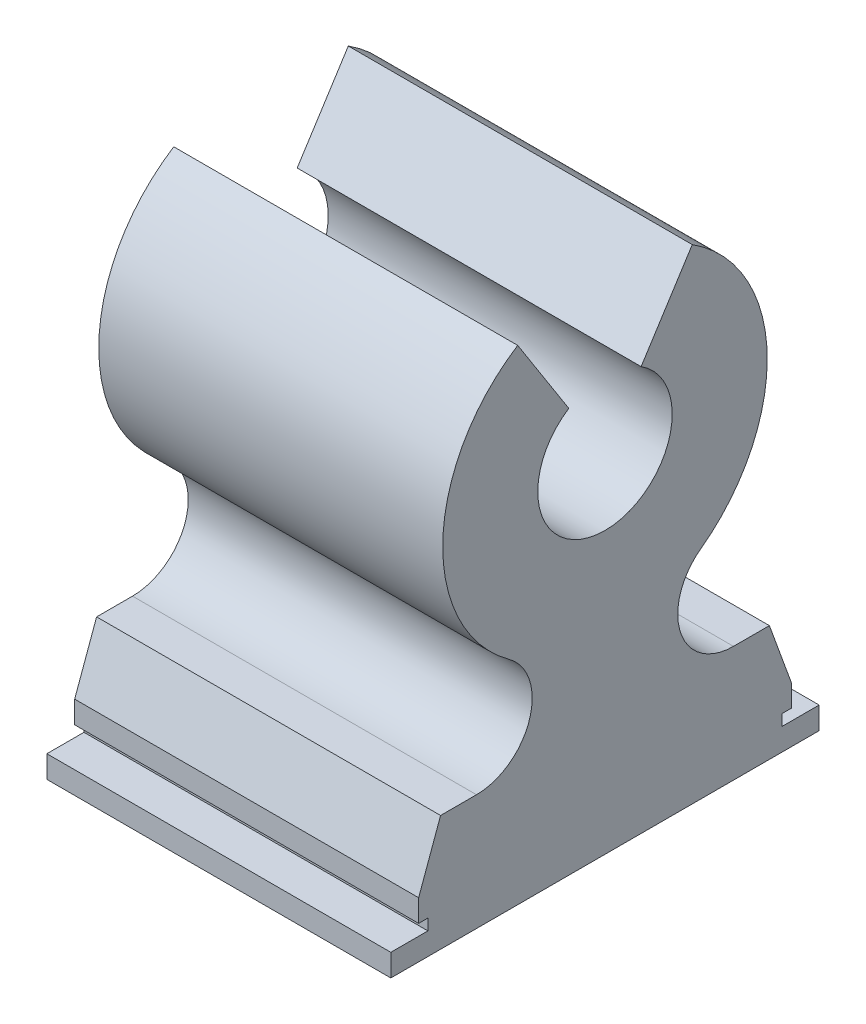
SolidWorks part; units mm, degrees
ref_plane "Plane1" through (0, 0, 0) normal (0, 0, 1) x (1, 0, 0)
ref_plane "Plane2" through (0, 0, 0) normal (0, 1, 0) x (1, 0, 0)
ref_plane "Plane3" through (0, 0, 0) normal (1, 0, 0) x (0, 0, -1)
sketch "BodySke" plane through (0, 0, 0) normal (1, 0, 0) x (0, 0, -1)
  line L0 (-5.8674, -9.525) -> (5.8674, -9.525)
  line L1 (5.8674, -9.525) -> (5.8674, -8.9154)
  line L2 (5.8674, -8.9154) -> (4.8514, -8.9154)
  line L3 (-5.8674, -9.525) -> (-5.8674, -8.9154)
  line L4 (-5.8674, -8.9154) -> (-4.8514, -8.9154)
  line L5 (4.8514, -8.9154) -> (4.8514, -8.6106)
  line L6 (-4.8514, -8.9154) -> (-4.8514, -8.6106)
  line L7 (4.8514, -8.6106) -> (5.1054, -8.6106)
  line L8 (-4.8514, -8.6106) -> (-5.1054, -8.6106)
  line L9 (-3.5204, -6.35) -> (-4.5045, -6.35)
  line L11 (4.5045, -6.35) -> (3.5204, -6.35)
  line L12 (0, 7.62) -> (0, -11.43) construction
  line L13 (7.62, 0) -> (-7.62, 0) construction
  line L14 (1.9939, -2.8908) -> (1.9939, -7.62) construction
  line L15 (-1.9939, -2.8908) -> (-1.9939, -7.62) construction
  line L16 (4.5045, -6.35) -> (5.1054, -8.001)
  line L17 (5.1054, -8.001) -> (5.1054, -8.6106)
  line L18 (-4.5045, -6.35) -> (-5.1054, -8.001)
  line L19 (-5.1054, -8.001) -> (-5.1054, -8.6106)
  line L20 (-0.9906, 1.5524) -> (-2.3911, 3.7471)
  line L21 (0.9906, 1.5524) -> (2.3911, 3.7471)
  arc A0 (-0.9906, 1.5524) -> (0.9906, 1.5524) centre (0, 0) ccw
  arc A1 (2.6205, -3.5904) -> (2.3911, 3.7471) centre (0, 0) ccw
  arc A2 (3.5204, -6.35) -> (2.6205, -3.5904) centre (3.5204, -4.8235) cw
  arc A3 (-2.6205, -3.5904) -> (-3.5204, -6.35) centre (-3.5204, -4.8235) cw
  arc A4 (-2.3911, 3.7471) -> (-2.6205, -3.5904) centre (0, 0) ccw
  dimension "Thread_min" = 3.683
  dimension "C_dia" = 8.89
  dimension "J_dim" = 3.9878
  dimension "E_dim" = 11.7348
  dimension "D_dim" = 3.175
  dimension "Clinch_ht" = 0.6096
  dimension "Side_ht" = 0.6096
  dimension "Groove_wid" = 0.3048
  dimension "A_dim" = 10.2108
  dimension "Groove_overall" = 9.7028
  dimension "F_dim" = 9.525
  dimension "D12" = 20
  dimension "H_dim" = 1.9812
extrude "Body" add sketch "BodySke" along normal blind 9.4234
cosmetic thread "ThreadCosmetic" [suppressed] parameters "Thread_nominal"=4.1656
equation "' \"Length@Body\" = 0.371"
equation "' \"A_dim@BodySke\" = 0.402"
equation "' \"C_dia@BodySke\" = 0.35"
equation "' \"D_dim@BodySke\" = 0.125"
equation "' \"E_dim@BodySke\" = 0.462"
equation "' \"F_dim@BodySke\" = 0.375"
equation "' \"H_dim@BodySke\" = 0.078"
equation "' \"J_dim@BodySke\" =  0.157"
equation "' \"J_dim@BodySke\" = 0.157"
equation "' \"Thread_min@BodySke\" = 0.145"
equation "\"Clinch_ht@BodySke\" = 0.04 * 0.6"
equation "\"Groove_wid@BodySke\" = \"Clinch_ht@BodySke\" / 2"
equation "\"Groove_overall@BodySke\" = \"A_dim@BodySke\" - ( \"E_dim@BodySke\" - \"A_dim@BodySke\") / 3"
equation "\"Side_ht@BodySke\" = \"Clinch_ht@BodySke\""
